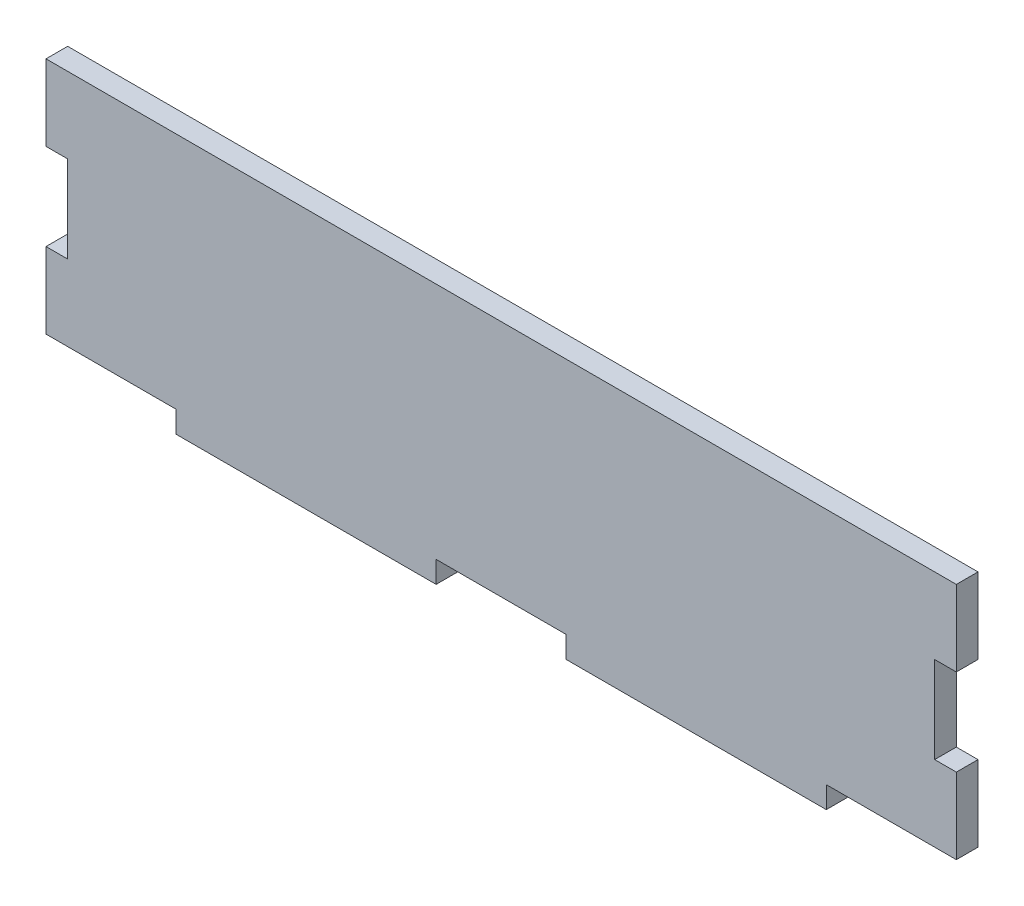
SolidWorks part; units mm, degrees
ref_plane "Plan de face" through (0, 0, 0) normal (0, 0, 1) x (1, 0, 0)
ref_plane "Plan de dessus" through (0, 0, 0) normal (0, 1, 0) x (1, 0, 0)
ref_plane "Plan de droite" through (0, 0, 0) normal (1, 0, 0) x (0, 0, -1)
sketch "Esquisse1" plane through (0, 0, 0) normal (0, 0, 1) x (1, 0, 0)
  line L23 (-54.7163, -171.0451) -> (155.2837, -171.0451)
  line L24 (155.2837, -171.0451) -> (155.2837, -188.5451)
  line L25 (155.2837, -188.5451) -> (150.2837, -188.5451)
  line L26 (150.2837, -188.5451) -> (150.2837, -208.5451)
  line L27 (150.2837, -208.5451) -> (155.2837, -208.5451)
  line L28 (155.2837, -208.5451) -> (155.2837, -226.0451)
  line L29 (155.2837, -226.0451) -> (125.2837, -226.0451)
  line L30 (125.2837, -226.0451) -> (125.2837, -231.0451)
  line L31 (125.2837, -231.0451) -> (65.2837, -231.0451)
  line L41 (-24.7163, -226.0451) -> (-54.7163, -226.0451)
  line L43 (65.2837, -231.0451) -> (65.2837, -226.0451)
  line L44 (65.2837, -226.0451) -> (35.2837, -226.0451)
  line L45 (35.2837, -226.0451) -> (35.2837, -231.0451)
  line L46 (35.2837, -231.0451) -> (-24.7163, -231.0451)
  line L47 (-24.7163, -231.0451) -> (-24.7163, -226.0451)
  line L48 (-54.7163, -226.0451) -> (-54.7163, -208.5451)
  line L49 (-54.7163, -208.5451) -> (-49.7163, -208.5451)
  line L50 (-49.7163, -208.5451) -> (-49.7163, -188.5451)
  line L51 (-49.7163, -188.5451) -> (-54.7163, -188.5451)
  line L52 (-54.7163, -188.5451) -> (-54.7163, -171.0451)
  dimension "D16" = 17.5
  dimension "D17" = 20
  dimension "D18" = 17.5
  dimension "D19" = 5
  dimension "D20" = 30
  dimension "D21" = 5
  dimension "D22" = 60
  dimension "D23" = 30
  dimension "D24" = 60
  dimension "D25" = 5
extrude "Boss.-Extru.1" add sketch "Esquisse1" along normal blind 5
